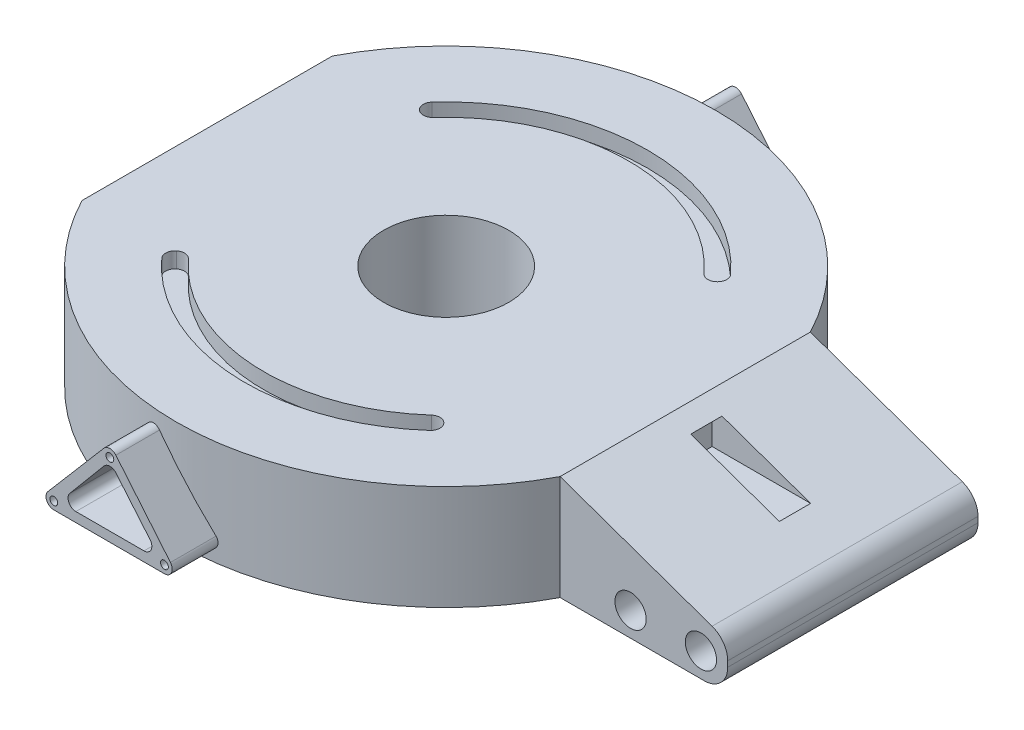
SolidWorks part; units mm, degrees
ref_plane "Front Plane" through (0, 0, 0) normal (0, 0, 1) x (1, 0, 0)
ref_plane "Top Plane" through (0, 0, 0) normal (0, 1, 0) x (1, 0, 0)
ref_plane "Right Plane" through (0, 0, 0) normal (1, 0, 0) x (0, 0, -1)
sketch "Sketch1" plane through (0, 0, 0) normal (0, 1, 0) x (1, 0, 0)
  line L0 (-152.8275, 80) -> (-152.8275, -80)
  line L5 (152.8275, 80) -> (152.8275, -80)
  circle A0 centre (0, 0) radius 40
  arc A5 (-152.8275, -80) -> (152.8275, -80) centre (0, 0) ccw
  arc A6 (152.8275, 80) -> (-152.8275, 80) centre (0, 0) ccw
  dimension "D1" = 80
  dimension "D2" = 345
  dimension "D3" = 160
extrude "Boss-Extrude1" add sketch "Sketch1" along normal blind 67
sketch "Sketch2" plane through (0, 67, 0) normal (0, 1, 0) x (1, 0, 0)
  line L0 (-94.8058, 77.7095) -> (-94.7666, 77.6773)
  line L1 (94.7666, 77.6773) -> (94.8058, 77.7095)
  line L2 (-94.8058, -77.7095) -> (-94.7666, -77.6773)
  line L3 (85.9309, -87.423) -> (85.8953, -87.3868)
  arc A0 (-95.4511, -86.3757) -> (85.6437, -96.1085) centre (0, 0) ccw
  arc A1 (-86.5142, -78.2917) -> (77.6247, -87.1132) centre (0, 0) ccw
  arc A2 (86.5142, 78.2917) -> (-86.5142, 78.2917) centre (0, 0) ccw
  arc A3 (95.4511, 86.3757) -> (-95.4511, 86.3757) centre (0, 0) ccw
  arc A4 (85.9309, -87.423) -> (85.6437, -96.1085) centre (81.6519, -91.629) cw
  arc A5 (85.8953, -87.3868) -> (77.6247, -87.1132) centre (81.6163, -91.5928) ccw
  arc A6 (94.8058, 77.7095) -> (95.4511, 86.3757) centre (91.0022, 82.3498) ccw
  arc A7 (94.7666, 77.6773) -> (86.5142, 78.2917) centre (90.963, 82.3177) cw
  arc A8 (-94.7666, -77.6773) -> (-86.5142, -78.2917) centre (-90.963, -82.3177) cw
  arc A9 (-94.8058, -77.7095) -> (-95.4511, -86.3757) centre (-91.0022, -82.3498) ccw
  arc A10 (-94.7666, 77.6773) -> (-86.5142, 78.2917) centre (-90.963, 82.3177) ccw
  arc A11 (-94.8058, 77.7095) -> (-95.4511, 86.3757) centre (-91.0022, 82.3498) cw
  point P16 (99.5596, 81.6061)
  point P19 (90.2397, 73.9668)
  dimension "D1" = 6
  dimension "D2" = 12.0507
extrude "Cut-Extrude1" cut sketch "Sketch2" against normal blind 10
sketch "Sketch3" plane through (0, 0, 0) normal (0, 0, 1) x (1, 0, 0)
  line L0 (152.8275, 67) -> (260, 29.183)
  line L1 (260, 29.183) -> (260, 0)
  line L2 (260, 0) -> (152.8275, 0)
  line L3 (152.8275, 67) -> (152.8275, 0)
  dimension "D1" = 260
extrude "Boss-Extrude2" add sketch "Sketch3" along normal mid plane 160
sketch "Sketch4" plane through (0, 0, 80) normal (0, 0, 1) x (1, 0, 0)
  circle A0 centre (197.8679, 15.4648) radius 10
  circle A1 centre (242.8679, 15.4648) radius 10
  point P4 (197.8679, 15.4648)
  dimension "D1" = 20
  dimension "D2" = 20
  dimension "D3" = 45
extrude "Cut-Extrude2" cut sketch "Sketch4" against normal up to next
fillet "Fillet1" radius 15 2 edges at (260, 0, 0) (260, 29.183, 0)
ref_plane "Plane1" through (160, 0, 0) normal (1, 0, 0) x (0, 0, -1)
sketch "Sketch6" plane through (160, 0, 0) normal (1, 0, 0) x (0, 0, -1)
  line L1 (-10, 62.2348) -> (10, 62.2348)
  line L2 (-10, 62.2348) -> (-10, 42.2348)
  line L3 (-10, 42.2348) -> (10, 42.2348)
  line L4 (10, 62.2348) -> (10, 42.2348)
  line L5 (-10, 62.2348) -> (10, 42.2348) construction
  line L6 (-10, 42.2348) -> (10, 62.2348) construction
  point P0 (0, 52.2348)
  point P5 (0, 46.2124)
  point P6 (0, 55.481)
  point P7 (0, 0)
  point P8 (0, 52.5955)
  point P9 (0, 52.2348)
  dimension "D1" = 20
  dimension "D2" = 20
extrude "Cut-Extrude5" cut sketch "Sketch6" along normal offset from surface (118.4415 mm away) 40
ref_plane "Plane2" through (0, 0, 200) normal (0, 0, 1) x (1, 0, 0)
sketch "Sketch7" plane through (0, 0, 200) normal (0, 0, 1) x (1, 0, 0)
  line L0 (-18.7983, 47.0083) -> (-40.5757, 21.055)
  line L1 (-36.7455, 12.841) -> (6.8094, 12.841)
  line L2 (10.6396, 21.055) -> (-11.1378, 47.0083)
  line L3 (-18.8204, 56.8723) -> (-54.6463, 14.9387)
  line L4 (-11.1751, 56.8222) -> (23.7105, 14.8886)
  line L5 (19.8668, 6.6909) -> (-50.8448, 6.6909)
  arc A0 (23.7105, 14.8886) -> (19.8668, 6.6909) centre (19.8668, 11.6909) cw
  arc A1 (6.8094, 12.841) -> (10.6396, 21.055) centre (6.8094, 17.841) ccw
  arc A2 (-40.5757, 21.055) -> (-36.7455, 12.841) centre (-36.7455, 17.841) ccw
  arc A3 (-54.6463, 14.9387) -> (-50.8448, 6.6909) centre (-50.8448, 11.6909) ccw
  arc A4 (-18.8204, 56.8723) -> (-11.1751, 56.8222) centre (-15.0189, 53.6245) cw
  arc A5 (-18.7983, 47.0083) -> (-11.1378, 47.0083) centre (-14.968, 43.7944) cw
  point P10 (17.532, 12.841)
  point P13 (-47.468, 12.841)
  dimension "D4" = 5
  dimension "D1" = 50
  dimension "D2" = 50
  dimension "D3" = 65
extrude "Boss-Extrude3" add sketch "Sketch7" against normal up to body separate body
sketch "Sketch8" plane through (0, 0, 200) normal (0, 0, 1) x (1, 0, 0)
  circle A0 centre (-15.0189, 53.6245) radius 2.5
  circle A1 centre (19.8668, 11.6909) radius 2.5
  circle A2 centre (-50.8448, 11.6909) radius 2.5
  point P9 (0, 0)
  dimension "D1" = 5
extrude "Cut-Extrude6" cut sketch "Sketch8" against normal blind 40
mirror "Mirror1" about plane through (0, 0, 0) normal (0, 0, 1) of "Cut-Extrude6", "Boss-Extrude3"
